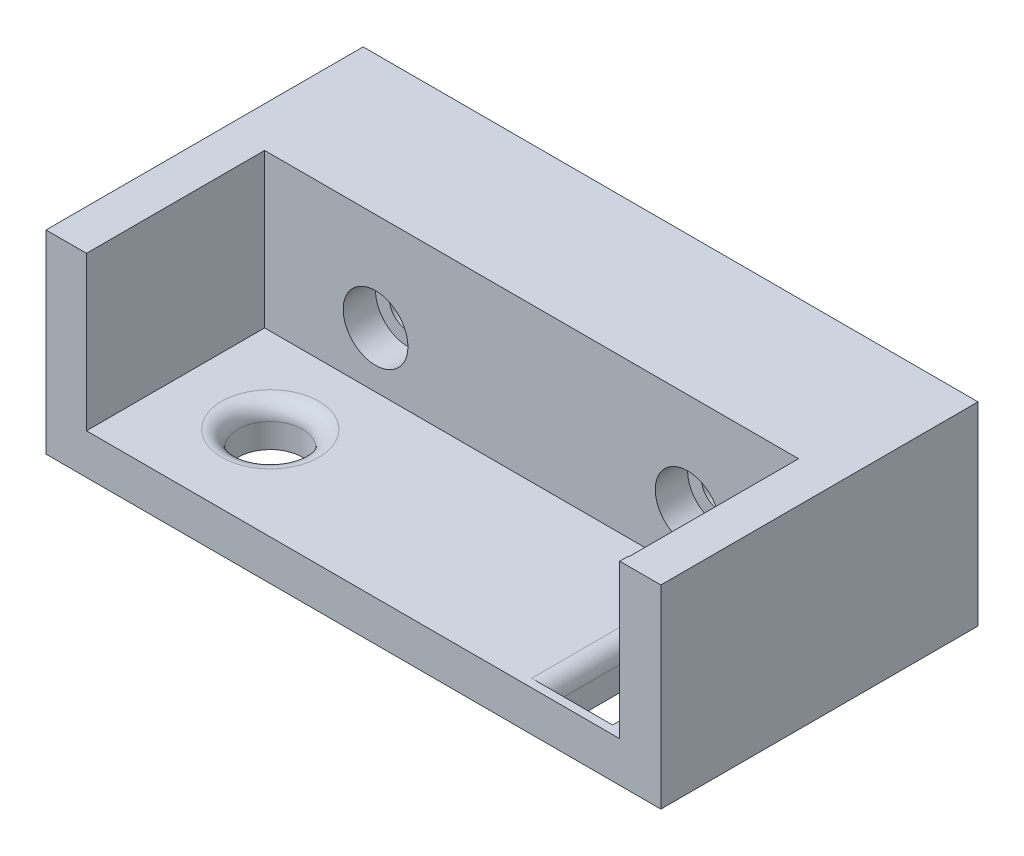
SolidWorks part; units mm, degrees
ref_plane "前基準面" through (0, 0, 0) normal (0, 0, 1) x (1, 0, 0)
ref_plane "上基準面" through (0, 0, 0) normal (0, 1, 0) x (1, 0, 0)
ref_plane "右基準面" through (0, 0, 0) normal (1, 0, 0) x (0, 0, -1)
sketch "草圖1" plane through (0, 0, 0) normal (0, 1, 0) x (1, 0, 0)
  line L1 (-33, 10.5) -> (33, 10.5)
  line L2 (-33, 10.5) -> (-33, -10.5)
  line L3 (-33, -10.5) -> (33, -10.5)
  line L4 (33, 10.5) -> (33, -10.5)
  line L5 (-33, 10.5) -> (33, -10.5) construction
  line L6 (-33, -10.5) -> (33, 10.5) construction
  line L7 (-38, 15.5) -> (38, 15.5)
  line L8 (-38, 15.5) -> (-38, -15.5)
  line L9 (-38, -15.5) -> (38, -15.5)
  line L10 (38, 15.5) -> (38, -15.5)
  line L11 (-38, 15.5) -> (38, -15.5) construction
  line L12 (-38, -15.5) -> (38, 15.5) construction
  point P0 (0, 0)
  point P6 (0, 0)
  dimension "D1" = 21
  dimension "D2" = 66
  dimension "D3" = 5
  dimension "D4" = 5
extrude "填料-伸長1" add sketch "草圖1" along normal blind 19
sketch "草圖3" plane through (0, 0, 0) normal (0, 1, 0) x (1, 0, 0)
  line L0 (-21.8, 0) -> (0, 0) construction
  line L1 (-38, 15.5) -> (38, 15.5)
  line L2 (-38, 15.5) -> (-38, -15.5)
  line L3 (-38, -15.5) -> (38, -15.5)
  line L4 (38, 15.5) -> (38, -15.5)
  line L5 (-38, 15.5) -> (38, -15.5) construction
  line L6 (-38, -15.5) -> (38, 15.5) construction
  line L7 (-33, 10.5) -> (-33, -10.5) construction
  line L9 (23, 12) -> (31, 12)
  line L10 (23, 12) -> (23, -10.5)
  line L11 (23, -10.5) -> (31, -10.5)
  line L12 (31, 12) -> (31, -10.5)
  line L13 (23, 12) -> (31, -10.5) construction
  line L14 (23, -10.5) -> (31, 12) construction
  line L15 (-33, -10.5) -> (33, -10.5) construction
  line L16 (33, -10.5) -> (33, 10.5) construction
  circle A0 centre (-21.8, 0) radius 4
  point P0 (0, 0)
  point P13 (27, 0.75)
  dimension "D1" = 8
  dimension "D2" = 11.2
  dimension "D3" = 8
  dimension "D4" = 2
extrude "填料-伸長3" add sketch "草圖3" against normal blind 5
ref_plane "平面1" through (-38, 0, 0) normal (-1, 0, 0) x (0, 0, 1)
sketch "草圖4" plane through (-38, 0, 0) normal (-1, 0, 0) x (0, 0, 1)
  line L0 (-15.5, 7) -> (0.0163, 7) construction
  line L1 (-3.2337, 8.8) -> (3.2663, 8.8)
  line L2 (-3.2337, 8.8) -> (-3.2337, 5.2)
  line L3 (-3.2337, 5.2) -> (3.2663, 5.2)
  line L4 (3.2663, 8.8) -> (3.2663, 5.2)
  line L5 (-3.2337, 8.8) -> (3.2663, 5.2) construction
  line L6 (-3.2337, 5.2) -> (3.2663, 8.8) construction
  line L7 (-15.5, 19) -> (-15.5, -5) construction
  point P0 (0.0163, 7)
  dimension "D1" = 6.5
  dimension "D2" = 3.6
extrude "除料-伸長1" [suppressed] cut sketch "草圖4" against normal blind 5
fillet "圓角1" radius 2 1 edges at (-21.8, 0, 4)
fillet "圓角2" radius 2 1 edges at (23, 0, 0)
sketch "草圖5" plane through (0, 0, 0) normal (0, 1, 0) x (1, 0, 0)
  line L0 (-38, 28.2614) -> (-38, -28.2614) construction
  line L1 (-38, -11.5225) -> (38.7589, -11.5225)
  line L2 (-38, -11.5225) -> (-38, -15.5)
  line L3 (-38, -15.5) -> (38.7589, -15.5)
  line L4 (38.7589, -11.5225) -> (38.7589, -15.5)
  line L5 (-38, -15.5) -> (38, -15.5) construction
extrude "除料-伸長2" cut sketch "草圖5" against normal through all both and the other way through all
ref_plane "平面2" through (0, 0, -27.6775) normal (0, 0, 1) x (1, 0, 0)
sketch "草圖6" plane through (0, 0, -27.6775) normal (0, 0, 1) x (1, 0, 0)
  line L0 (-38, 28.2614) -> (-38, -28.2614) construction
  line L1 (-38, 19) -> (38, 19)
  line L2 (-38, 19) -> (-38, -5)
  line L3 (-38, -5) -> (38, -5)
  line L4 (38, 19) -> (38, -5)
  line L5 (38, 19) -> (-38, 19) construction
  line L6 (38, 19) -> (38, -5) construction
  line L7 (38, -5) -> (-38, -5) construction
extrude "填料-伸長4" add sketch "草圖6" along normal up to surface (12.1775 mm away) up to face at (0, 7, -15.5)
sketch "草圖7" plane through (0, 0, -27.6775) normal (0, 0, 1) x (1, 0, 0)
  line L0 (-38, 28.2614) -> (-38, -28.2614) construction
  line L1 (-38, 19) -> (-48, 19)
  line L2 (-38, 19) -> (-38, -5)
  line L3 (-38, -5) -> (-48, -5)
  line L4 (-48, 19) -> (-48, -5)
  line L5 (38, 19) -> (-38, 19) construction
  line L6 (38, -5) -> (-38, -5) construction
  line L7 (-42.8115, 7.1154) -> (-43, 19) construction
  line L8 (-42.8115, 7.1154) -> (-48, 7) construction
  line L9 (0, 0) -> (0, 6.0302) construction
  circle A0 centre (-42.8115, 7.1154) radius 2.19
  dimension "D1" = 4.38
  dimension "D2" = 10
extrude "填料-伸長5" [suppressed] add sketch "草圖7" along normal blind 4.6
sketch "草圖8" plane through (0, 0, -27.6775) normal (0, 0, 1) x (1, 0, 0)
  line L0 (0, -0.5997) -> (0, 0) construction
  line L1 (0, 0) -> (0, 12.3747) construction
  circle A0 centre (19.2879, 6.8518) radius 2.3
  circle A1 centre (-19.2879, 6.8518) radius 2.3
  dimension "D1" = 4.6
extrude "除料-伸長5" cut sketch "草圖8" along normal through all
sketch "草圖12" plane through (0, 19, 0) normal (0, 1, 0) x (1, 0, 0)
  line L0 (-32.4901, 27.6775) -> (-32.4901, -11.5225)
  line L1 (-16.7398, 27.6775) -> (16.7398, 27.6775) construction
  line L2 (38, -11.5225) -> (-38, -11.5225) construction
sketch "草圖13" plane through (0, 19, 0) normal (0, 1, 0) x (1, 0, 0)
  line L0 (38, -11.5225) -> (-38, -11.5225) construction
  line L1 (-33, -10.5) -> (32.912, -10.5)
  line L2 (-33, -10.5) -> (-33, -11.5225)
  line L3 (-33, -11.5225) -> (32.912, -11.5225)
  line L4 (32.912, -10.5) -> (32.912, -11.5225)
extrude "除料-伸長6" cut sketch "草圖13" against normal up to surface (19 mm away) up to face at (-21.8, 0, 6)
sketch "草圖14" plane through (0, 0, -10.5) normal (0, 0, 1) x (1, 0, 0)
  circle A0 centre (-19.2879, 6.8518) radius 4
  circle A1 centre (19.2879, 6.8518) radius 4
  dimension "D1" = 8
  dimension "D2" = 8
extrude "除料-伸長7" cut sketch "草圖14" against normal blind 4
